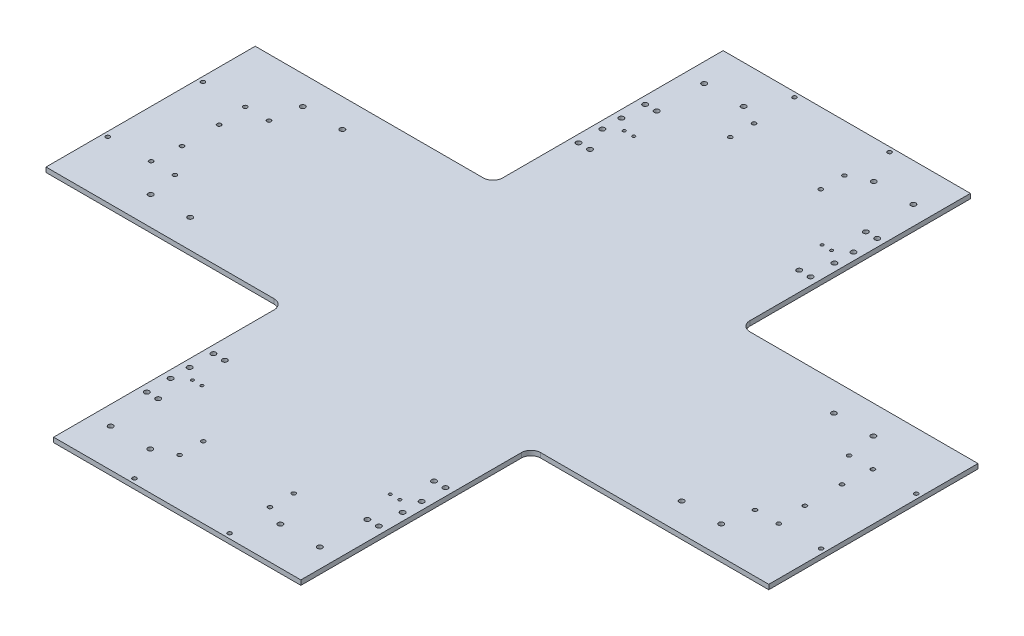
SolidWorks part; units mm, degrees
material "3.0205 (EN-AW 1200)"
ref_plane "前视基准面" through (0, 0, 0) normal (0, 0, 1) x (1, 0, 0)
ref_plane "上视基准面" through (0, 0, 0) normal (0, 1, 0) x (1, 0, 0)
ref_plane "右视基准面" through (0, 0, 0) normal (1, 0, 0) x (0, 0, -1)
other "Configuration Table"
sketch "Sketch1" plane through (0, 0, 0) normal (0, 1, 0) x (1, 0, 0)
  line L0 (130, 352) -> (-130, 352)
  line L1 (-130, 352) -> (-130, 110)
  line L2 (-130, 110) -> (-380, 110)
  line L5 (-380, 110) -> (-380, -110)
  line L6 (0, 352) -> (0, -66.8675) construction
  line L7 (-380, 0) -> (131.0517, 0) construction
  line L8 (380, 110) -> (380, -110)
  line L11 (130, 110) -> (380, 110)
  line L12 (130, 352) -> (130, 110)
  line L13 (130, -352) -> (130, -110)
  line L14 (130, -110) -> (380, -110)
  line L19 (-130, -110) -> (-380, -110)
  line L20 (-130, -352) -> (-130, -110)
  line L21 (130, -352) -> (-130, -352)
  point P21 (380, 0)
  dimension "D1" = 130
  dimension "D2" = 250
  dimension "D3" = 110
  dimension "D4" = 242
extrude "Boss-Extrude1" add sketch "Sketch1" along normal blind 5
sketch "Sketch2" plane through (0, 5, 0) normal (0, 1, 0) x (1, 0, 0)
  line L2 (380, 110) -> (130, 110) construction
  line L3 (380, -110) -> (380, 110) construction
  line L4 (-56.7455, 0) -> (47.5165, 0) construction
  line L5 (0, 54.7142) -> (0, -64.2255) construction
  line L6 (130, 110) -> (130, 352) construction
  line L7 (130, 352) -> (-130, 352) construction
  circle A0 centre (330, 49.5) radius 2.125
  circle A1 centre (305, 49.5) radius 2.125
  circle A2 centre (327.5, 19.5) radius 2.125
  circle A6 centre (327.5, -19.5) radius 2.125
  circle A7 centre (305, -49.5) radius 2.125
  circle A8 centre (330, -49.5) radius 2.125
  circle A9 centre (-330, -49.5) radius 2.125
  circle A10 centre (-305, -49.5) radius 2.125
  circle A11 centre (-327.5, -19.5) radius 2.125
  circle A12 centre (-327.5, 19.5) radius 2.125
  circle A13 centre (-305, 49.5) radius 2.125
  circle A14 centre (-330, 49.5) radius 2.125
  circle A15 centre (47.5, 302) radius 2.125
  circle A16 centre (47.5, 277) radius 2.125
  circle A17 centre (-47.5, 277) radius 2.125
  circle A18 centre (-47.5, 302) radius 2.125
  circle A19 centre (-47.5, -302) radius 2.125
  circle A20 centre (-47.5, -277) radius 2.125
  circle A21 centre (47.5, -277) radius 2.125
  circle A22 centre (47.5, -302) radius 2.125
  dimension "D1" = 60.5
  dimension "D3" = 52.5
  dimension "D5" = 4.25
  dimension "D7" = 4.25
  dimension "D8" = 4.25
  dimension "D9" = 4.25
  dimension "D10" = 4.25
  dimension "D2" = 90.5
  dimension "D4" = 25
  dimension "D6" = 50
  dimension "D11" = 82.5
  dimension "D12" = 50
  dimension "D13" = 25
extrude "Cut-Extrude1" cut sketch "Sketch2" against normal blind 3
sketch "Sketch4" plane through (0, 5, 0) normal (0, 1, 0) x (1, 0, 0)
  line L0 (-130, 352) -> (-130, 110) construction
  line L1 (130, 352) -> (-130, 352) construction
  line L2 (0, 46.9886) -> (0, -40.2904) construction
  line L3 (-35.103, 0) -> (92.4951, 0) construction
  line L5 (130, -352) -> (130, -110) construction
  circle A0 centre (-122, 192) radius 2.6
  circle A1 centre (-110, 192) radius 2.6
  circle A2 centre (-122, 217) radius 2.6
  circle A3 centre (-122, 237) radius 2.6
  circle A4 centre (-122, 262) radius 2.6
  circle A5 centre (-110, 262) radius 2.6
  circle A6 centre (110, 262) radius 2.6
  circle A7 centre (122, 262) radius 2.6
  circle A8 centre (122, 237) radius 2.6
  circle A9 centre (122, 217) radius 2.6
  circle A10 centre (110, 192) radius 2.6
  circle A11 centre (122, 192) radius 2.6
  circle A12 centre (122, -192) radius 2.6
  circle A13 centre (110, -192) radius 2.6
  circle A14 centre (122, -217) radius 2.6
  circle A15 centre (122, -237) radius 2.6
  circle A16 centre (122, -262) radius 2.6
  circle A17 centre (110, -262) radius 2.6
  circle A18 centre (-110, -262) radius 2.6
  circle A19 centre (-122, -262) radius 2.6
  circle A20 centre (-122, -237) radius 2.6
  circle A21 centre (-122, -217) radius 2.6
  circle A22 centre (-110, -192) radius 2.6
  circle A23 centre (-122, -192) radius 2.6
  circle A24 centre (109, -227) radius 1.6
  circle A25 centre (-109, -227) radius 1.6
  circle A26 centre (109, 227) radius 1.6
  circle A27 centre (-109, 227) radius 1.6
  circle A28 centre (99, -227) radius 1.6
  circle A29 centre (-99, -227) radius 1.6
  circle A30 centre (99, 227) radius 1.6
  circle A31 centre (-99, 227) radius 1.6
  dimension "D3" = 5.2
  dimension "D4" = 5.2
  dimension "D5" = 8
  dimension "D6" = 8
  dimension "D9" = 5.2
  dimension "D10" = 5.2
  dimension "D11" = 5.2
  dimension "D12" = 5.2
  dimension "D19" = 3.2
  dimension "D20" = 21
  dimension "D21" = 10
  dimension "D22" = 3.2
  dimension "D23" = 10
  dimension "D1" = 8
  dimension "D2" = 20
  dimension "D7" = 8
  dimension "D8" = 20
  dimension "D13" = 25
  dimension "D14" = 20
  dimension "D15" = 25
  dimension "D16" = 25
  dimension "D17" = 90
  dimension "D18" = 0
extrude "Cut-Extrude3" cut sketch "Sketch4" against normal blind 10
sketch "Sketch5" plane through (0, 5, 0) normal (0, 1, 0) x (1, 0, 0)
  line L0 (130, 352) -> (-130, 352) construction
  line L2 (-130, 352) -> (-130, 110) construction
  line L4 (130, 110) -> (130, 352) construction
  line L5 (-46.9195, 0) -> (66.6223, 0) construction
  line L6 (0, 59.0569) -> (0, -54.4849) construction
  line L10 (-380, 110) -> (-380, -110) construction
  line L12 (-130, 110) -> (-380, 110) construction
  line L13 (-380, -110) -> (-130, -110) construction
  circle A0 centre (-50, 347) radius 2.1
  circle A1 centre (50, 347) radius 2.1
  circle A2 centre (50, -347) radius 2.1
  circle A3 centre (-50, -347) radius 2.1
  circle A4 centre (-375, 50) radius 2.1
  circle A5 centre (-375, -50) radius 2.1
  circle A6 centre (375, -50) radius 2.1
  circle A7 centre (375, 50) radius 2.1
  dimension "D1" = 4.2
  dimension "D2" = 4.2
  dimension "D3" = 60
  dimension "D6" = 4.2
  dimension "D7" = 4.2
  dimension "5" = 5
  dimension "D4" = 80
  dimension "D5" = 80
  dimension "D8" = 60
  dimension "D9" = 5
  dimension "D10" = 5
extrude "Cut-Extrude4" cut sketch "Sketch5" against normal blind 10
fillet "Fillet1" radius 10 4 edges at (-130, 2.5, -110) (-130, 2.5, 110) (130, 2.5, 110) (130, 2.5, -110)
sketch "Sketch6" plane through (0, 5, 0) normal (0, 1, 0) x (1, 0, 0)
  line L0 (130, 352) -> (-130, 352) construction
  line L1 (-130, 352) -> (-130, 120) construction
  line L3 (0, 50.3702) -> (0, -42.7646) construction
  line L4 (-54.8568, 0) -> (91.2004, 0) construction
  line L5 (380, 110) -> (140, 110) construction
  line L6 (380, -110) -> (380, 110) construction
  circle A0 centre (-110, 312) radius 2.6
  circle A1 centre (-68.4, 312) radius 2.6
  circle A4 centre (68.4, 312) radius 2.6
  circle A5 centre (110, 312) radius 2.6
  circle A6 centre (110, -312) radius 2.6
  circle A7 centre (68.4, -312) radius 2.6
  circle A8 centre (-68.4, -312) radius 2.6
  circle A9 centre (-110, -312) radius 2.6
  circle A10 centre (258.4, 80) radius 2.6
  circle A11 centre (300, 80) radius 2.6
  circle A12 centre (300, -80) radius 2.6
  circle A13 centre (258.4, -80) radius 2.6
  circle A14 centre (-258.4, -80) radius 2.6
  circle A15 centre (-300, -80) radius 2.6
  circle A16 centre (-300, 80) radius 2.6
  circle A17 centre (-258.4, 80) radius 2.6
  dimension "D1" = 5.2
  dimension "D2" = 5.2
  dimension "D3" = 5.2
  dimension "D4" = 5.2
  dimension "D5" = 40
  dimension "D8" = 30
  dimension "D6" = 20
  dimension "D7" = 41.6
  dimension "D9" = 80
  dimension "D10" = 41.6
extrude "Cut-Extrude5" cut sketch "Sketch6" against normal blind 10
